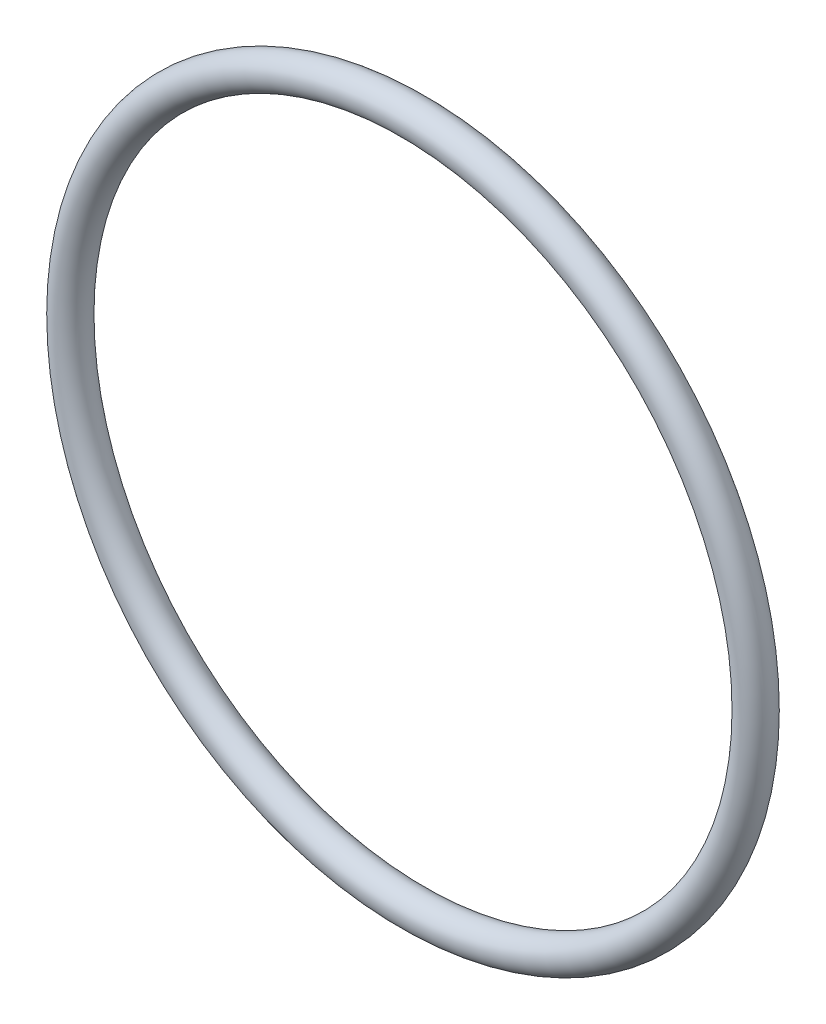
SolidWorks part; units mm, degrees
ref_plane "Front" through (0, 0, 0) normal (0, 0, 1) x (1, 0, 0)
ref_plane "Top" through (0, 0, 0) normal (0, 1, 0) x (1, 0, 0)
ref_plane "Right" through (0, 0, 0) normal (1, 0, 0) x (0, 0, -1)
sketch "Sketch1" plane through (0, 0, 0) normal (1, 0, 0) x (0, -1, 0)
  line L0 (0, -0.889) -> (0, 0.889) construction
  line L2 (-21.0109, 0) -> (21.0109, 0) construction
  line L3 (-17.3228, 0) -> (17.3228, 0) construction
  circle A0 centre (18.2118, 0) radius 0.889
  point P9 (17.3228, 0)
  point P10 (19.1008, 0)
  point P13 (18.2118, 0.889)
  point P14 (18.2118, -0.889)
  dimension "Width" = 1.778
  dimension "ID" = 34.6456
revolve "Revolve1" add sketch "Sketch1" angle 360 about L0
sketch "Sketch2" plane through (0, 0, 0) normal (0, 0, 1) x (1, 0, 0)
  line L0 (0, 17.3228) -> (0, -17.3228) construction
  circle A0 centre (0, 0) radius 18.1674 construction
